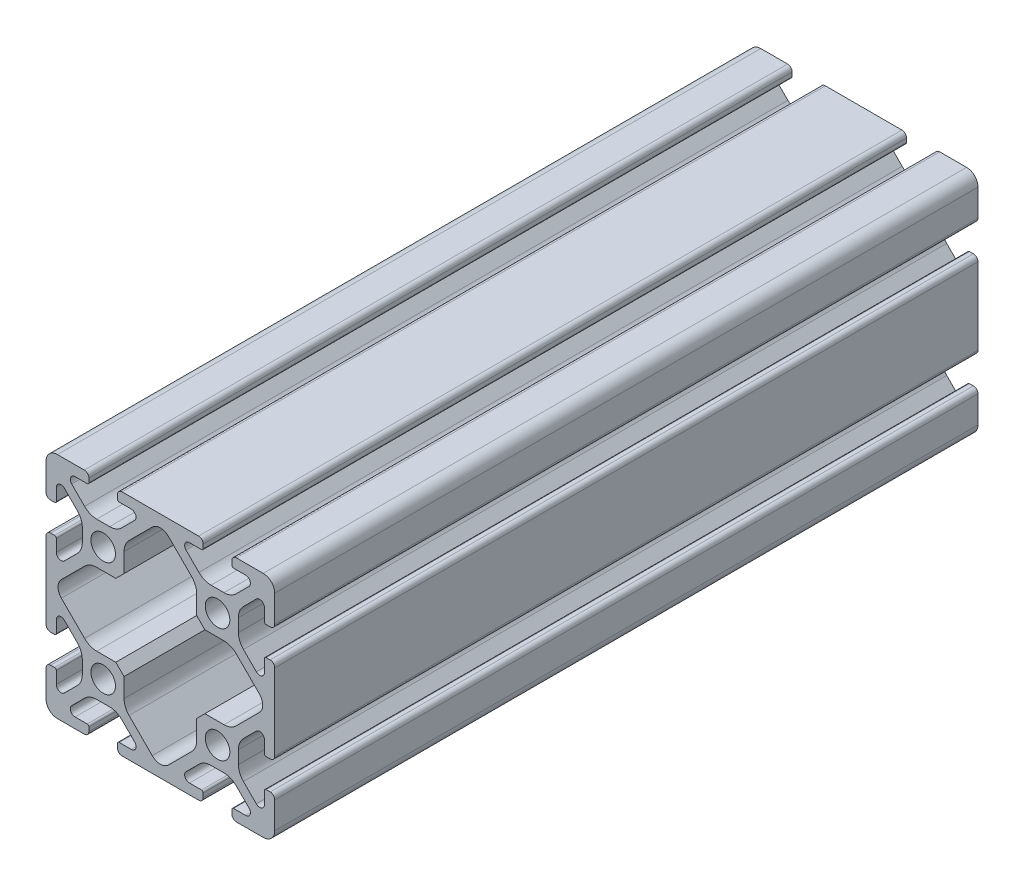
SolidWorks part; units mm, degrees
material "Alliage 1060"
ref_plane "Plan de face" through (0, 0, 0) normal (0, 0, 1) x (1, 0, 0)
ref_plane "Plan de dessus" through (0, 0, 0) normal (0, 1, 0) x (1, 0, 0)
ref_plane "Plan de droite" through (0, 0, 0) normal (1, 0, 0) x (0, 0, -1)
ref_plane "Plan1" through (0, 0, 0) normal (0, 0, -1) x (-1, 0, 0)
sketch "Esquisse1" plane through (0, 0, 0) normal (0, 0, -1) x (-1, 0, 0)
  line L0 (0, 13.3) -> (0, 26.7)
  line L1 (-0.8, 27.5) -> (-1.5, 27.5)
  line L2 (-1.8, 27.2) -> (-1.8, 25.0816)
  line L3 (-3.2196, 24.4936) -> (-5.4713, 26.7453)
  line L4 (-6.35, 28.8666) -> (-6.35, 31.1334)
  line L5 (-5.4713, 33.2547) -> (-3.2196, 35.5064)
  line L6 (-1.8, 34.9184) -> (-1.8, 32.8)
  line L7 (-1.5, 32.5) -> (-0.8, 32.5)
  line L8 (0, 33.3) -> (0, 38)
  line L9 (-2, 40) -> (-6.7, 40)
  line L10 (-7.5, 39.2) -> (-7.5, 38.5)
  line L11 (-7.2, 38.2) -> (-5.0816, 38.2)
  line L12 (-4.4936, 36.7804) -> (-6.7453, 34.5287)
  line L13 (-8.8666, 33.65) -> (-11.1334, 33.65)
  line L14 (-13.2547, 34.5287) -> (-15.5064, 36.7804)
  line L15 (-14.9184, 38.2) -> (-12.8, 38.2)
  line L16 (-12.5, 38.5) -> (-12.5, 39.2)
  line L17 (-13.3, 40) -> (-26.7, 40)
  line L18 (-27.5, 39.2) -> (-27.5, 38.5)
  line L19 (-27.2, 38.2) -> (-25.0816, 38.2)
  line L20 (-24.4936, 36.7804) -> (-26.7453, 34.5287)
  line L21 (-28.8666, 33.65) -> (-31.1334, 33.65)
  line L22 (-33.2547, 34.5287) -> (-35.5064, 36.7804)
  line L23 (-34.9184, 38.2) -> (-32.8, 38.2)
  line L24 (-32.5, 38.5) -> (-32.5, 39.2)
  line L25 (-33.3, 40) -> (-38, 40)
  line L26 (-40, 38) -> (-40, 33.3)
  line L27 (-39.2, 32.5) -> (-38.5, 32.5)
  line L28 (-38.2, 32.8) -> (-38.2, 34.9184)
  line L29 (-36.7804, 35.5064) -> (-34.5287, 33.2547)
  line L30 (-33.65, 31.1334) -> (-33.65, 28.8666)
  line L31 (-34.5287, 26.7453) -> (-36.7804, 24.4936)
  line L32 (-38.2, 25.0816) -> (-38.2, 27.2)
  line L33 (-38.5, 27.5) -> (-39.2, 27.5)
  line L34 (-40, 26.7) -> (-40, 13.3)
  line L35 (-39.2, 12.5) -> (-38.5, 12.5)
  line L36 (-38.2, 12.8) -> (-38.2, 14.9184)
  line L37 (-36.7804, 15.5064) -> (-34.5287, 13.2547)
  line L38 (-33.65, 11.1334) -> (-33.65, 8.8666)
  line L39 (-34.5287, 6.7453) -> (-36.7804, 4.4936)
  line L40 (-38.2, 5.0816) -> (-38.2, 7.2)
  line L41 (-38.5, 7.5) -> (-39.2, 7.5)
  line L42 (-40, 6.7) -> (-40, 2)
  line L43 (-38, 0) -> (-33.3, 0)
  line L44 (-32.5, 0.8) -> (-32.5, 1.5)
  line L45 (-32.8, 1.8) -> (-34.9184, 1.8)
  line L46 (-35.5064, 3.2196) -> (-33.2547, 5.4713)
  line L47 (-31.1334, 6.35) -> (-28.8666, 6.35)
  line L48 (-26.7453, 5.4713) -> (-24.4936, 3.2196)
  line L49 (-25.0816, 1.8) -> (-27.2, 1.8)
  line L50 (-27.5, 1.5) -> (-27.5, 0.8)
  line L51 (-26.7, 0) -> (-13.3, 0)
  line L52 (-12.5, 0.8) -> (-12.5, 1.5)
  line L53 (-12.8, 1.8) -> (-14.9184, 1.8)
  line L54 (-15.5064, 3.2196) -> (-13.2547, 5.4713)
  line L55 (-11.1334, 6.35) -> (-8.8666, 6.35)
  line L56 (-6.7453, 5.4713) -> (-4.4936, 3.2196)
  line L57 (-5.0816, 1.8) -> (-7.2, 1.8)
  line L58 (-7.5, 1.5) -> (-7.5, 0.8)
  line L59 (-6.7, 0) -> (-2, 0)
  line L60 (0, 2) -> (0, 6.7)
  line L61 (-0.8, 7.5) -> (-1.5, 7.5)
  line L62 (-1.8, 7.2) -> (-1.8, 5.0816)
  line L63 (-3.2196, 4.4936) -> (-5.4713, 6.7453)
  line L64 (-6.35, 8.8666) -> (-6.35, 11.1334)
  line L65 (-5.4713, 13.2547) -> (-3.2196, 15.5064)
  line L66 (-1.8, 14.9184) -> (-1.8, 12.8)
  line L67 (-1.5, 12.5) -> (-0.8, 12.5)
  line L68 (-12.2079, 13.65) -> (-13.65, 12.2079)
  line L69 (-13.65, 12.2079) -> (-13.65, 8.8654)
  line L70 (-14.5287, 6.7441) -> (-18.5858, 2.687)
  line L71 (-21.4142, 2.687) -> (-25.4713, 6.7441)
  line L72 (-26.35, 8.8654) -> (-26.35, 12.2079)
  line L73 (-26.35, 12.2079) -> (-27.0711, 12.9289)
  line L74 (-27.0711, 12.9289) -> (-27.7921, 13.65)
  line L75 (-27.7921, 13.65) -> (-31.1346, 13.65)
  line L76 (-33.2559, 14.5287) -> (-37.313, 18.5858)
  line L77 (-37.313, 21.4142) -> (-33.2559, 25.4713)
  line L78 (-31.1346, 26.35) -> (-27.7921, 26.35)
  line L79 (-27.7921, 26.35) -> (-27.0711, 27.0711)
  line L80 (-27.0711, 27.0711) -> (-26.35, 27.7921)
  line L81 (-26.35, 27.7921) -> (-26.35, 31.1346)
  line L82 (-25.4713, 33.2559) -> (-21.4142, 37.313)
  line L83 (-18.5858, 37.313) -> (-14.5287, 33.2559)
  line L84 (-13.65, 31.1346) -> (-13.65, 27.7921)
  line L85 (-13.65, 27.7921) -> (-12.2079, 26.35)
  line L86 (-12.2079, 26.35) -> (-8.8654, 26.35)
  line L87 (-6.7441, 25.4713) -> (-2.687, 21.4142)
  line L88 (-2.687, 18.5858) -> (-6.7441, 14.5287)
  line L89 (-8.8654, 13.65) -> (-12.2079, 13.65)
  arc A0 (-0.8, 12.5) -> (0, 13.3) centre (-0.8, 13.3) ccw
  arc A1 (0, 26.7) -> (-0.8, 27.5) centre (-0.8, 26.7) ccw
  arc A2 (-1.5, 27.5) -> (-1.8, 27.2) centre (-1.5, 27.2) ccw
  arc A3 (-1.8, 25.0816) -> (-3.2196, 24.4936) centre (-2.6316, 25.0816) cw
  arc A4 (-5.4713, 26.7453) -> (-6.35, 28.8666) centre (-3.35, 28.8666) cw
  arc A5 (-6.35, 31.1334) -> (-5.4713, 33.2547) centre (-3.35, 31.1334) cw
  arc A6 (-3.2196, 35.5064) -> (-1.8, 34.9184) centre (-2.6316, 34.9184) cw
  arc A7 (-1.8, 32.8) -> (-1.5, 32.5) centre (-1.5, 32.8) ccw
  arc A8 (-0.8, 32.5) -> (0, 33.3) centre (-0.8, 33.3) ccw
  arc A9 (0, 38) -> (-2, 40) centre (-2, 38) ccw
  arc A10 (-6.7, 40) -> (-7.5, 39.2) centre (-6.7, 39.2) ccw
  arc A11 (-7.5, 38.5) -> (-7.2, 38.2) centre (-7.2, 38.5) ccw
  arc A12 (-5.0816, 38.2) -> (-4.4936, 36.7804) centre (-5.0816, 37.3684) cw
  arc A13 (-6.7453, 34.5287) -> (-8.8666, 33.65) centre (-8.8666, 36.65) cw
  arc A14 (-11.1334, 33.65) -> (-13.2547, 34.5287) centre (-11.1334, 36.65) cw
  arc A15 (-15.5064, 36.7804) -> (-14.9184, 38.2) centre (-14.9184, 37.3684) cw
  arc A16 (-12.8, 38.2) -> (-12.5, 38.5) centre (-12.8, 38.5) ccw
  arc A17 (-12.5, 39.2) -> (-13.3, 40) centre (-13.3, 39.2) ccw
  arc A18 (-26.7, 40) -> (-27.5, 39.2) centre (-26.7, 39.2) ccw
  arc A19 (-27.5, 38.5) -> (-27.2, 38.2) centre (-27.2, 38.5) ccw
  arc A20 (-25.0816, 38.2) -> (-24.4936, 36.7804) centre (-25.0816, 37.3684) cw
  arc A21 (-26.7453, 34.5287) -> (-28.8666, 33.65) centre (-28.8666, 36.65) cw
  arc A22 (-31.1334, 33.65) -> (-33.2547, 34.5287) centre (-31.1334, 36.65) cw
  arc A23 (-35.5064, 36.7804) -> (-34.9184, 38.2) centre (-34.9184, 37.3684) cw
  arc A24 (-32.8, 38.2) -> (-32.5, 38.5) centre (-32.8, 38.5) ccw
  arc A25 (-32.5, 39.2) -> (-33.3, 40) centre (-33.3, 39.2) ccw
  arc A26 (-38, 40) -> (-40, 38) centre (-38, 38) ccw
  arc A27 (-40, 33.3) -> (-39.2, 32.5) centre (-39.2, 33.3) ccw
  arc A28 (-38.5, 32.5) -> (-38.2, 32.8) centre (-38.5, 32.8) ccw
  arc A29 (-38.2, 34.9184) -> (-36.7804, 35.5064) centre (-37.3684, 34.9184) cw
  arc A30 (-34.5287, 33.2547) -> (-33.65, 31.1334) centre (-36.65, 31.1334) cw
  arc A31 (-33.65, 28.8666) -> (-34.5287, 26.7453) centre (-36.65, 28.8666) cw
  arc A32 (-36.7804, 24.4936) -> (-38.2, 25.0816) centre (-37.3684, 25.0816) cw
  arc A33 (-38.2, 27.2) -> (-38.5, 27.5) centre (-38.5, 27.2) ccw
  arc A34 (-39.2, 27.5) -> (-40, 26.7) centre (-39.2, 26.7) ccw
  arc A35 (-40, 13.3) -> (-39.2, 12.5) centre (-39.2, 13.3) ccw
  arc A36 (-38.5, 12.5) -> (-38.2, 12.8) centre (-38.5, 12.8) ccw
  arc A37 (-38.2, 14.9184) -> (-36.7804, 15.5064) centre (-37.3684, 14.9184) cw
  arc A38 (-34.5287, 13.2547) -> (-33.65, 11.1334) centre (-36.65, 11.1334) cw
  arc A39 (-33.65, 8.8666) -> (-34.5287, 6.7453) centre (-36.65, 8.8666) cw
  arc A40 (-36.7804, 4.4936) -> (-38.2, 5.0816) centre (-37.3684, 5.0816) cw
  arc A41 (-38.2, 7.2) -> (-38.5, 7.5) centre (-38.5, 7.2) ccw
  arc A42 (-39.2, 7.5) -> (-40, 6.7) centre (-39.2, 6.7) ccw
  arc A43 (-40, 2) -> (-38, 0) centre (-38, 2) ccw
  arc A44 (-33.3, 0) -> (-32.5, 0.8) centre (-33.3, 0.8) ccw
  arc A45 (-32.5, 1.5) -> (-32.8, 1.8) centre (-32.8, 1.5) ccw
  arc A46 (-34.9184, 1.8) -> (-35.5064, 3.2196) centre (-34.9184, 2.6316) cw
  arc A47 (-33.2547, 5.4713) -> (-31.1334, 6.35) centre (-31.1334, 3.35) cw
  arc A48 (-28.8666, 6.35) -> (-26.7453, 5.4713) centre (-28.8666, 3.35) cw
  arc A49 (-24.4936, 3.2196) -> (-25.0816, 1.8) centre (-25.0816, 2.6316) cw
  arc A50 (-27.2, 1.8) -> (-27.5, 1.5) centre (-27.2, 1.5) ccw
  arc A51 (-27.5, 0.8) -> (-26.7, 0) centre (-26.7, 0.8) ccw
  arc A52 (-13.3, 0) -> (-12.5, 0.8) centre (-13.3, 0.8) ccw
  arc A53 (-12.5, 1.5) -> (-12.8, 1.8) centre (-12.8, 1.5) ccw
  arc A54 (-14.9184, 1.8) -> (-15.5064, 3.2196) centre (-14.9184, 2.6316) cw
  arc A55 (-13.2547, 5.4713) -> (-11.1334, 6.35) centre (-11.1334, 3.35) cw
  arc A56 (-8.8666, 6.35) -> (-6.7453, 5.4713) centre (-8.8666, 3.35) cw
  arc A57 (-4.4936, 3.2196) -> (-5.0816, 1.8) centre (-5.0816, 2.6316) cw
  arc A58 (-7.2, 1.8) -> (-7.5, 1.5) centre (-7.2, 1.5) ccw
  arc A59 (-7.5, 0.8) -> (-6.7, 0) centre (-6.7, 0.8) ccw
  arc A60 (-2, 0) -> (0, 2) centre (-2, 2) ccw
  arc A61 (0, 6.7) -> (-0.8, 7.5) centre (-0.8, 6.7) ccw
  arc A62 (-1.5, 7.5) -> (-1.8, 7.2) centre (-1.5, 7.2) ccw
  arc A63 (-1.8, 5.0816) -> (-3.2196, 4.4936) centre (-2.6316, 5.0816) cw
  arc A64 (-5.4713, 6.7453) -> (-6.35, 8.8666) centre (-3.35, 8.8666) cw
  arc A65 (-6.35, 11.1334) -> (-5.4713, 13.2547) centre (-3.35, 11.1334) cw
  arc A66 (-3.2196, 15.5064) -> (-1.8, 14.9184) centre (-2.6316, 14.9184) cw
  arc A67 (-1.8, 12.8) -> (-1.5, 12.5) centre (-1.5, 12.8) ccw
  circle A68 centre (-10, 10) radius 2.15
  circle A69 centre (-10, 30) radius 2.15
  circle A70 centre (-30, 10) radius 2.15
  circle A71 centre (-30, 30) radius 2.15
  arc A72 (-13.65, 8.8654) -> (-14.5287, 6.7441) centre (-16.65, 8.8654) cw
  arc A73 (-18.5858, 2.687) -> (-21.4142, 2.687) centre (-20, 4.1012) cw
  arc A74 (-25.4713, 6.7441) -> (-26.35, 8.8654) centre (-23.35, 8.8654) cw
  arc A75 (-31.1346, 13.65) -> (-33.2559, 14.5287) centre (-31.1346, 16.65) cw
  arc A76 (-37.313, 18.5858) -> (-37.313, 21.4142) centre (-35.8988, 20) cw
  arc A77 (-33.2559, 25.4713) -> (-31.1346, 26.35) centre (-31.1346, 23.35) cw
  arc A78 (-26.35, 31.1346) -> (-25.4713, 33.2559) centre (-23.35, 31.1346) cw
  arc A79 (-21.4142, 37.313) -> (-18.5858, 37.313) centre (-20, 35.8988) cw
  arc A80 (-14.5287, 33.2559) -> (-13.65, 31.1346) centre (-16.65, 31.1346) cw
  arc A81 (-8.8654, 26.35) -> (-6.7441, 25.4713) centre (-8.8654, 23.35) cw
  arc A82 (-2.687, 21.4142) -> (-2.687, 18.5858) centre (-4.1012, 20) cw
  arc A83 (-6.7441, 14.5287) -> (-8.8654, 13.65) centre (-8.8654, 16.65) cw
extrude "Extrusion1" add sketch "Esquisse1" against normal blind 123
